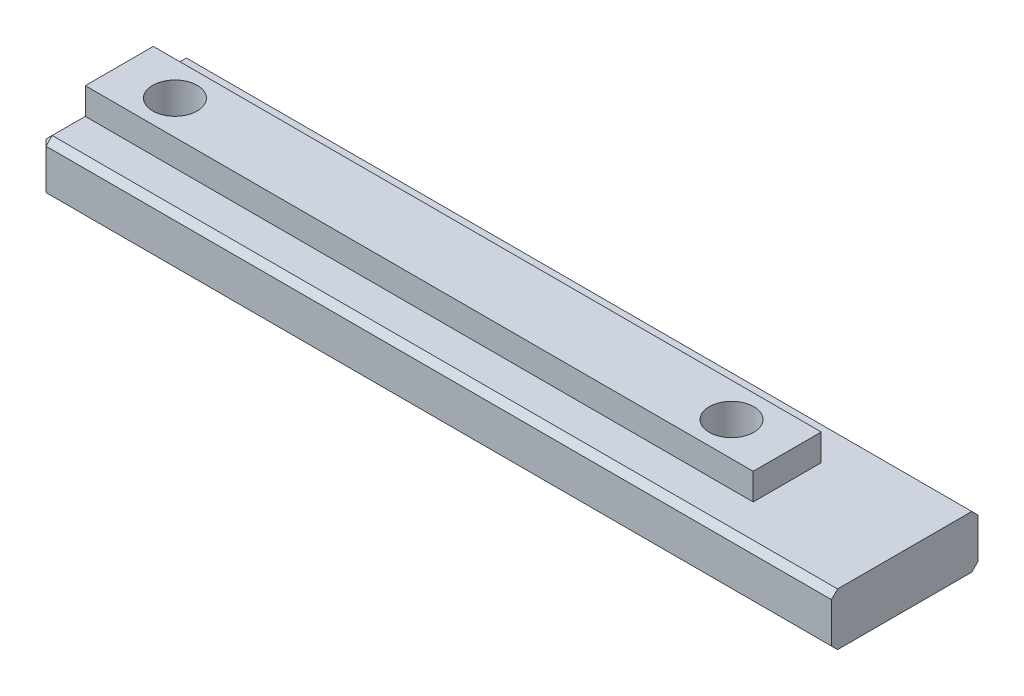
SolidWorks part; units mm, degrees
ref_plane "Front Plane" through (0, 0, 0) normal (0, 0, 1) x (1, 0, 0)
ref_plane "Top Plane" through (0, 0, 0) normal (0, 1, 0) x (1, 0, 0)
ref_plane "Right Plane" through (0, 0, 0) normal (1, 0, 0) x (0, 0, -1)
sketch "Sketch1" plane through (0, 0, 0) normal (0, 1, 0) x (1, 0, 0)
  line L1 (-27.5, 5.925) -> (27.5, 5.925)
  line L2 (-27.5, 5.925) -> (-27.5, -5.925)
  line L3 (-27.5, -5.925) -> (27.5, -5.925)
  line L4 (27.5, 5.925) -> (27.5, -5.925)
  line L5 (-27.5, 5.925) -> (27.5, -5.925) construction
  line L6 (-27.5, -5.925) -> (27.5, 5.925) construction
  point P0 (0, 0)
  dimension "D1" = 11.85
  dimension "D2" = 55
extrude "Boss-Extrude1" add sketch "Sketch1" along normal blind 4.25
sketch "Sketch2" plane through (0, 0, 0) normal (0, -1, 0) x (1, 0, 0)
  line L0 (-22.5, 0) -> (22.5, 0) construction
  point P3 (0, 0)
  point P5 (-22.5, 0)
  point P6 (22.5, 0)
  dimension "D1" = 45
chamfer "Chamfer1" distance 0.5 angle 45 9 edges at (0, 4.25, 5.925) (-27.5, 4.25, 0) (0, 4.25, -5.925) (27.5, 4.25, 0) (0, 0, 5.925) (0, 0, -5.925) (-27.5, 2.125, 5.925) (-27.5, 2.125, -5.925) (-27.5, 0, 0)
sketch "Sketch7" plane through (0, 0, 0) normal (1, 0, 0) x (0, 0, -1)
  line L1 (-2.75, 4.25) -> (2.75, 4.25)
  line L2 (-2.75, 4.25) -> (-2.75, 6.4)
  line L3 (-2.75, 6.4) -> (2.75, 6.4)
  line L4 (2.75, 4.25) -> (2.75, 6.4)
  line L6 (-5.425, 4.25) -> (5.425, 4.25) construction
  point P7 (0, 4.25)
  point P8 (0, 4.25)
  dimension "D1" = 5.5
  dimension "D2" = 2.15
extrude "Boss-Extrude2" add sketch "Sketch7" along normal up to vertex (27 mm away) and the other way up to vertex (27 mm away)
hole_wizard "CBORE for M3 SHCS1" positions "Sketch5" profile "Sketch6" counterbore size "M3" standard "ANSI Metric" end condition through all
sketch "Sketch5" plane through (0, 0, 0) normal (0, -1, 0) x (-1, 0, 0)
  point P0 (-22.5, 0)
  point P3 (22.5, 0)
sketch "Sketch6" plane through (22.5, 0, 0) normal (1, 0, 0) x (0, 0, -1)
  line L0 (0, 0) -> (0, 6.4)
  line L1 (0, 6.4) -> (1.8, 6.4)
  line L3 (1.8, 6.4) -> (1.8, 2.2)
  line L4 (3.25, 2.2) -> (1.8, 2.2)
  line L5 (3.25, 2.2) -> (3.25, 0.025)
  line L6 (3.25, 0.025) -> (3.275, 0)
  line L7 (3.275, 0) -> (0, 0)
  line L8 (-3.25, 0.025) -> (-3.275, 0) construction
  line L11 (0, -6.35) -> (0, 107.95) construction
  dimension "Thru Hole Dia." = 3.6
  dimension "Thru Hole Depth" = 6.4
  dimension "C'Bore Dia." = 6.5
  dimension "C'Bore Depth" = 2.2
  dimension "Near C'Sink Dia." = 6.55
  dimension "Near C'Sink Angle" = 90
sketch "Sketch8" plane through (27.5, 0, 0) normal (1, 0, 0) x (0, 0, -1)
  line L8 (5.425, 4.25) -> (-5.425, 4.25)
  line L9 (-5.425, 4.25) -> (-5.925, 3.75)
  line L10 (-5.925, 3.75) -> (-5.925, 0.5)
  line L11 (-5.925, 0.5) -> (-5.425, 0)
  line L12 (-5.425, 0) -> (5.425, 0)
  line L13 (5.425, 0) -> (5.925, 0.5)
  line L14 (5.925, 0.5) -> (5.925, 3.75)
  line L15 (5.925, 3.75) -> (5.425, 4.25)
  line L16 (5.425, 4.25) -> (-5.425, 4.25)
  line L17 (-5.425, 4.25) -> (-5.925, 3.75)
  line L18 (-5.925, 3.75) -> (-5.925, 0.5)
  line L19 (-5.925, 0.5) -> (-5.425, 0)
  line L20 (-5.425, 0) -> (5.425, 0)
  line L21 (5.425, 0) -> (5.925, 0.5)
  line L22 (5.925, 0.5) -> (5.925, 3.75)
  line L23 (5.925, 3.75) -> (5.425, 4.25)
  dimension "D1" = 0
extrude "Boss-Extrude3" add sketch "Sketch8" along normal blind 9
sketch "Sketch10" plane through (0, 0, 0) normal (0, 0, 1) x (1, 0, 0)
  line L0 (36.5, 0) -> (-27, 0) construction
  line L1 (31.15, 0) -> (34.45, 0)
  line L2 (31.15, 0) -> (31.15, 2.5)
  line L3 (31.15, 2.5) -> (34.45, 2.5)
  line L4 (34.45, 0) -> (34.45, 2.5)
  line L5 (31.2, -0.5) -> (31.2, 1.7) construction
  dimension "D1" = 0.05
  dimension "D2" = 2.5
  dimension "D3" = 3.3
extrude "Cut-Extrude1" cut sketch "Sketch10" against normal blind 2 and the other way blind 2
